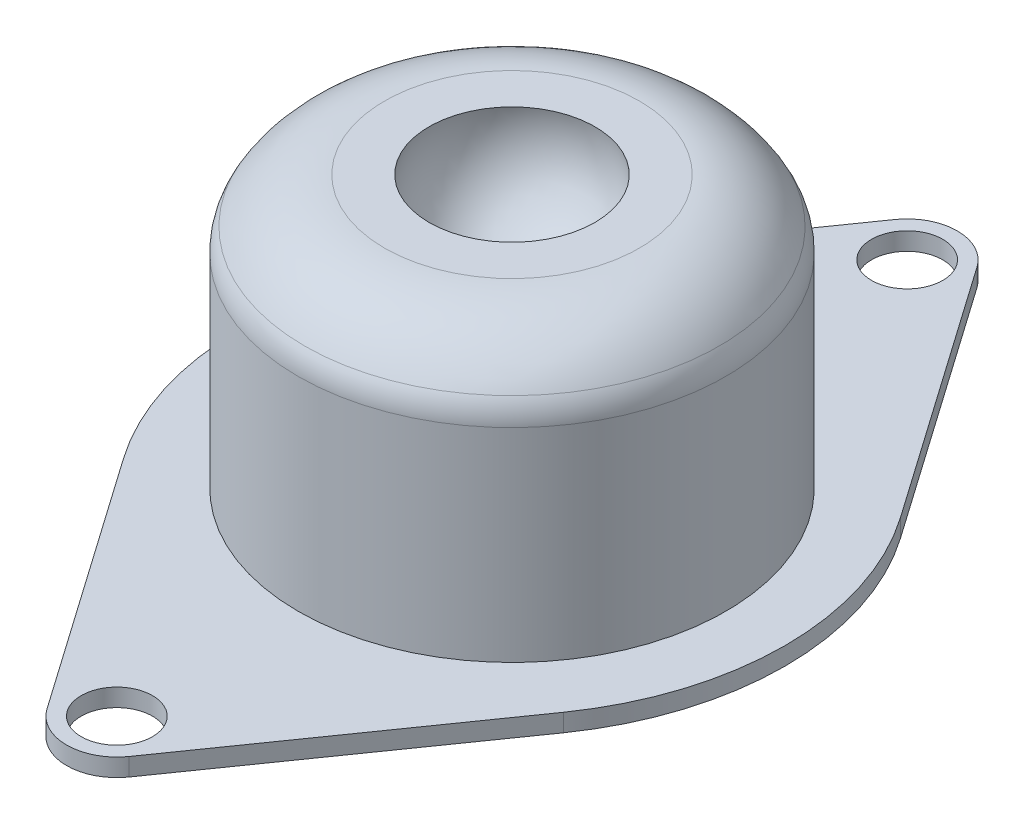
SolidWorks part; units mm, degrees
material "201.0-T6 Insulated Mold Casting (SS)"
ref_plane "Front Plane" through (0, 0, 0) normal (0, 0, 1) x (1, 0, 0)
ref_plane "Top Plane" through (0, 0, 0) normal (0, 1, 0) x (1, 0, 0)
ref_plane "Right Plane" through (0, 0, 0) normal (1, 0, 0) x (0, 0, -1)
sketch "Sketch1" plane through (0, 0, 0) normal (0, 1, 0) x (1, 0, 0)
  line L0 (-2.3068, 23.7992) -> (-12.3444, 9.464)
  line L1 (0, 25) -> (0, -25) construction
  line L2 (0, 0) -> (-15.3283, 0) construction
  line L3 (2.3068, 23.7992) -> (12.3444, 9.464)
  line L4 (2.3068, -23.7992) -> (12.3444, -9.464)
  line L5 (-2.3068, -23.7992) -> (-12.3444, -9.464)
  arc A0 (-2.3068, 23.7992) -> (2.3068, 23.7992) centre (0, 22.184) cw
  arc A1 (-12.3444, 9.464) -> (-12.3444, -9.464) centre (1.1717, 0) ccw
  arc A2 (12.3444, 9.464) -> (12.3444, -9.464) centre (-1.1717, 0) cw
  arc A3 (-2.3068, -23.7992) -> (2.3068, -23.7992) centre (0, -22.184) ccw
  dimension "D2" = 16.5
  dimension "D1" = 35
  dimension "D3" = 50
  dimension "D4" = 17.5
extrude "Boss-Extrude1" add sketch "Sketch1" along normal blind 1
sketch "Sketch3" plane through (0, 0, 0) normal (0, 0, 1) x (1, 0, 0)
  line L0 (0, 1) -> (12, 1)
  line L1 (12, 1) -> (12, 13)
  line L4 (15.3283, 1) -> (12.3444, 1) construction
  line L5 (7.1563, 16.2375) -> (4.6563, 16.2375)
  line L6 (0, 10.475) -> (0, 1)
  circle A0 centre (0, 15.2375) radius 4.7625 construction
  arc A1 (4.6563, 16.2375) -> (0, 10.475) centre (0, 15.2375) cw
  arc A2 (7.1563, 16.2375) -> (12, 13) centre (7.1563, 10.9954) cw
  point P2 (0, 20)
  point P10 (4.6563, 16.2375)
  dimension "D3" = 9.525
  dimension "D1" = 12
  dimension "D2" = 1
  dimension "D4" = 20
  dimension "D5" = 12
  dimension "D6" = 2.5
revolve "Revolve1" add sketch "Sketch3" angle 360 about L6
fillet "Fillet2" radius 2.5 1 edges at (0, 13, 12)
sketch "Sketch4" plane through (0, 1, 0) normal (0, 1, 0) x (1, 0, 0)
  circle A0 centre (0, -22.184) radius 2
  circle A1 centre (0, 22.184) radius 2
  arc A2 (-2.3068, -23.7992) -> (2.3068, -23.7992) centre (0, -22.184) ccw construction
  arc A3 (2.3068, 23.7992) -> (-2.3068, 23.7992) centre (0, 22.184) ccw construction
  dimension "D1" = 4
extrude "Cut-Extrude1" cut sketch "Sketch4" against normal through all
